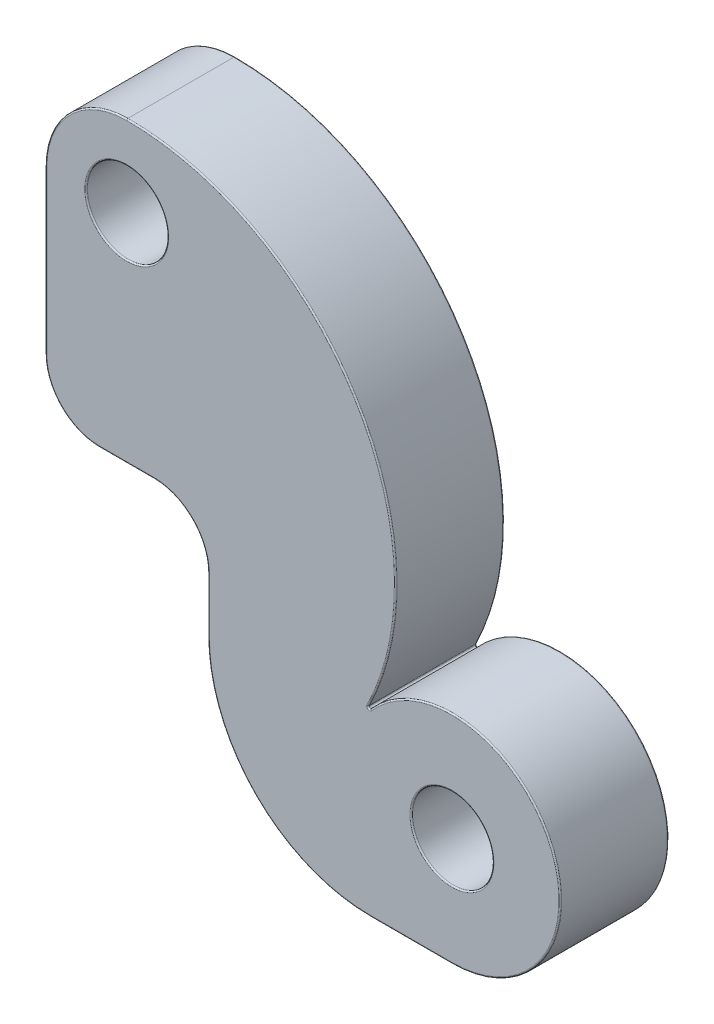
SolidWorks part; units mm, degrees
ref_plane "Front Plane" through (0, 0, 0) normal (0, 0, 1) x (1, 0, 0)
ref_plane "Top Plane" through (0, 0, 0) normal (0, 1, 0) x (1, 0, 0)
ref_plane "Right Plane" through (0, 0, 0) normal (1, 0, 0) x (0, 0, -1)
sketch "Sketch1" plane through (0, 0, 0) normal (0, 0, 1) x (1, 0, 0)
  line L0 (0, 0) -> (0, -50000) construction
  line L1 (-15, 0) -> (-15, -30)
  line L2 (-5, -40) -> (5, -40)
  line L3 (15, -50) -> (15, -60)
  line L4 (60, -90) -> (45, -90)
  circle A0 centre (0, 0) radius 7.5
  arc A1 (0, 15) -> (-15, 0) centre (0, 0) ccw
  arc A2 (60, -90) -> (42.7692, -59.8462) centre (60, -70) ccw
  circle A3 centre (60, -70) radius 7.5
  arc A4 (5, -40) -> (15, -50) centre (5, -50) cw
  arc A5 (-15, -30) -> (-5, -40) centre (-5, -30) ccw
  arc A6 (45, -90) -> (15, -60) centre (45, -60) cw
  arc A7 (0, 15) -> (42.7692, -59.8462) centre (0, -34.6429) cw
  point P19 (15, -40)
  point P22 (-15, -40)
  dimension "D1" = 15
  dimension "D2" = 30
  dimension "D3" = 40
  dimension "D4" = 15
  dimension "D9" = 10
  dimension "D10" = 30
  dimension "D5" = 60
  dimension "D6" = 40
  dimension "D7" = 70
  dimension "D8" = 30
extrude "Boss-Extrude1" add sketch "Sketch1" along normal blind 20
fillet "Fillet1" radius 0.25 25 edges at (52.5, -90, 0) (0, -40, 0) (67.5, -70, 0) (67.5, -70, 20) (7.5, 0, 0) (7.5, 0, 20) (-10.6066, 10.6066, 0) (-15, -15, 0) (-12.0711, -37.0711, 0) (12.0711, -42.9289, 0) (15, -55, 0) (23.7868, -81.2132, 0) (77.3649, -60.0772, 0) (43.1021, -10.0131, 0) (-10.6066, 10.6066, 20) (-15, -15, 20) (-12.0711, -37.0711, 20) (0, -40, 20) (12.0711, -42.9289, 20) (15, -55, 20) (23.7868, -81.2132, 20) (52.5, -90, 20) (77.3649, -60.0772, 20) (43.1021, -10.0131, 20) (42.7692, -59.8462, 10)
